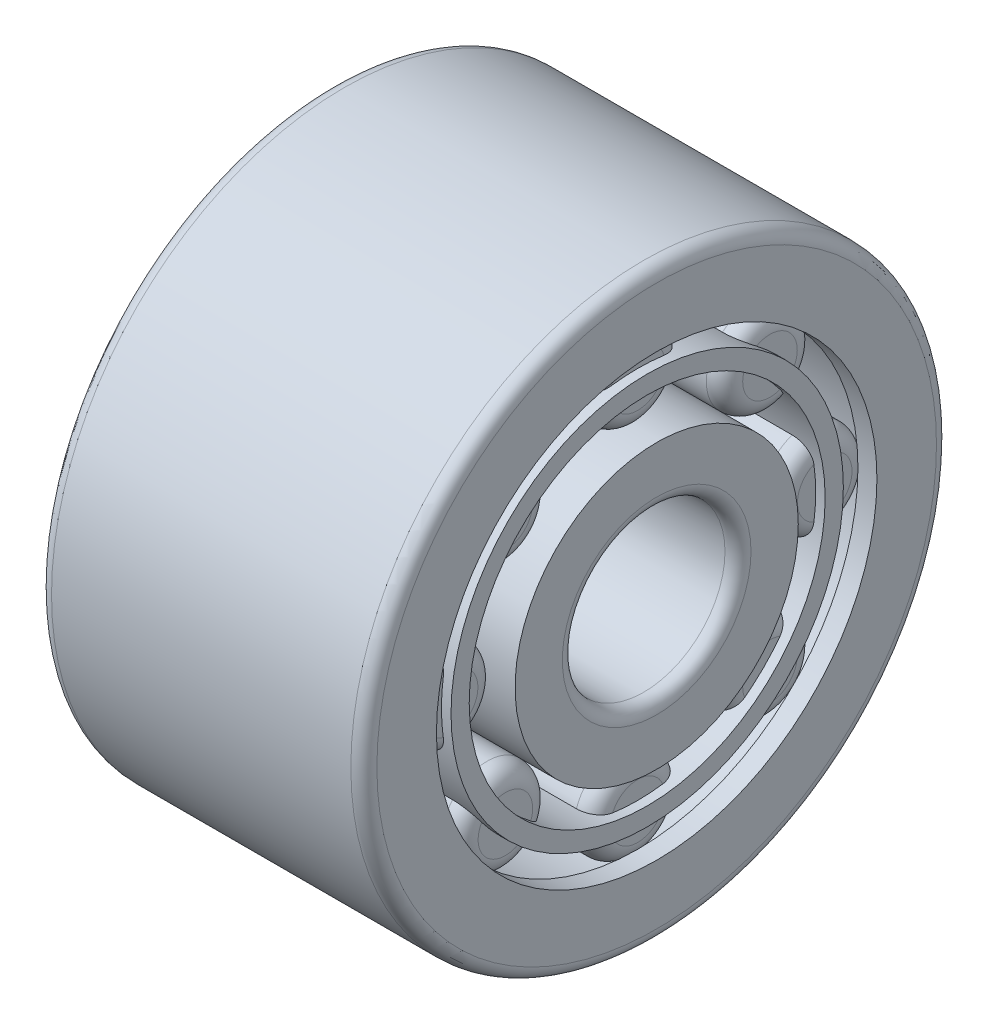
SolidWorks part; units mm, degrees
ref_plane "Plane1" through (0, 0, 0) normal (0, 0, 1) x (1, 0, 0)
ref_plane "Plane2" through (0, 0, 0) normal (0, 1, 0) x (1, 0, 0)
ref_plane "Plane3" through (0, 0, 0) normal (1, 0, 0) x (0, 0, -1)
sketch "Clipboard" plane through (0, 0, 0) normal (0, 0, 1) x (1, 0, 0)
  line L0 (-10, 0) -> (10, 0) construction
  line L1 (0, 0) -> (27.3694, -3.8465)
  line L2 (0, 0) -> (36.1572, 5.0816)
  line L3 (0, 0) -> (44.9449, -6.3166)
  line L4 (0, 0) -> (-22.3471, -0.7804)
  dimension "Race_OD" = 45.3866
  dimension "CLdia" = 36.5125
  dimension "Count" = 8
  dimension "Show_count" = 8
  dimension "Max_count" = 8
  dimension "Min_count" = 2
  dimension "Race_ID" = 27.6384
sketch "OutRacSke" plane through (0, 0, 0) normal (0, 0, 1) x (1, 0, 0)
  line L0 (-14.0229, 22.6933) -> (-14.0229, 21.4933)
  line L1 (-14.0229, 21.4933) -> (-15.875, 21.4933)
  line L2 (-15.875, 21.4933) -> (-15.875, 27.305)
  line L3 (-14.605, 28.575) -> (14.605, 28.575)
  line L4 (15.875, 27.305) -> (15.875, 21.4933)
  line L5 (15.875, 21.4933) -> (14.0229, 21.4933)
  line L6 (14.0229, 21.4933) -> (14.0229, 22.6933)
  line L7 (14.0229, 22.6933) -> (-14.0229, 22.6933)
  line L8 (-7.9375, 0) -> (7.9375, 0) construction
  arc A0 (-15.875, 27.305) -> (-14.605, 28.575) centre (-14.605, 27.305) cw
  arc A1 (14.605, 28.575) -> (15.875, 27.305) centre (14.605, 27.305) cw
  dimension "Radius" = 1.27
  dimension "OD" = 57.15
  dimension "Cyl_Len" = 28.0458
  dimension "Width" = 31.75
  dimension "halfWidth" = 15.875
  dimension "D1" = 14.0229
  dimension "Groove_Dp" = 1.2
  dimension "Race_OD" = 45.3866
revolve "OuterRace" add sketch "OutRacSke" angle 360 about L8
sketch "RolDetSke" plane through (0, 0, 0) normal (0, 0, 1) x (1, 0, 0)
  line L0 (-14.0229, 20.9188) -> (-14.0229, 18.2562)
  line L1 (-14.0229, 18.2562) -> (14.0229, 18.2562)
  line L2 (14.0229, 18.2562) -> (14.0229, 20.9188)
  line L3 (12.2479, 22.6938) -> (-12.2479, 22.6938)
  line L4 (-28.575, 18.2562) -> (28.575, 18.2562) construction
  arc A0 (14.0229, 20.9188) -> (12.2479, 22.6938) centre (12.2479, 20.9188) ccw
  arc A1 (-12.2479, 22.6938) -> (-14.0229, 20.9188) centre (-12.2479, 20.9188) ccw
  dimension "Cyl_Len" = 28.0458
  dimension "radius" = 1.775
  dimension "CLRad" = 18.2562
  dimension "Roller_diameter" = 8.8751
  dimension "halfCylLen" = 14.0229
revolve "RollerDetailed" add sketch "RolDetSke" angle 360 about L4
ref_axis "Axis1" through (-50, 0, 0) along (1, 0, 0)
sketch "RolSimSke" plane through (0, 25.4, 0) normal (0, 0, 1) x (1, 0, 0)
  line L0 (-14.0229, -4.4807) -> (-14.0229, -9.8058)
  line L1 (-25.4, -25.4) -> (25.4, -25.4) construction
  line L2 (14.0229, -9.8058) -> (14.0229, -4.4807)
  line L3 (12.2479, -2.7057) -> (-12.2479, -2.7057)
  line L5 (12.2479, -11.5808) -> (-12.2479, -11.5808)
  arc A0 (14.0229, -4.4807) -> (12.2479, -2.7057) centre (12.2479, -4.4807) ccw
  arc A1 (-12.2479, -2.7057) -> (-14.0229, -4.4807) centre (-12.2479, -4.4807) ccw
  arc A2 (14.0229, -9.8058) -> (12.2479, -11.5808) centre (12.2479, -9.8058) cw
  arc A3 (-12.2479, -11.5808) -> (-14.0229, -9.8058) centre (-12.2479, -9.8058) cw
  dimension "radius" = 1.775
  dimension "Roller_diameter" = 8.8751
  dimension "Bore" = 27.6384
  dimension "Cyl_Len" = 28.0458
  dimension "halfLength" = 14.0229
revolve "RollersSimplified" [suppressed] add sketch "RolSimSke" angle 360 about L1
sketch "InsRacSke" plane through (0, 0, 0) normal (0, 0, 1) x (1, 0, 0)
  line L2 (-15.875, 13.8192) -> (-15.875, 9.2075)
  line L4 (-14.605, 7.9375) -> (14.605, 7.9375)
  line L5 (15.875, 9.2075) -> (15.875, 13.8192)
  line L8 (15.875, 13.8192) -> (-15.875, 13.8192)
  line L9 (-7.9375, 0) -> (7.9375, 0) construction
  arc A0 (-15.875, 9.2075) -> (-14.605, 7.9375) centre (-14.605, 9.2075) ccw
  arc A2 (14.605, 7.9375) -> (15.875, 9.2075) centre (14.605, 9.2075) ccw
  dimension "halfWidth" = 15.875
  dimension "Race_ID" = 27.6384
  dimension "radius" = 1.27
  dimension "Bore" = 15.875
  dimension "Width_IR" = 31.75
revolve "InnerRace" add sketch "InsRacSke" angle 360 about L9
sketch "CagSpiSke" plane through (0, 0, 0) normal (0, 0, 1) x (1, 0, 0)
  line L0 (-17.1595, 0) -> (17.1595, 0) construction
  line L3 (-14.949, 17.3687) -> (14.949, 17.3687)
  line L4 (-14.949, 17.3687) -> (-14.949, 19.1438)
  line L5 (-14.949, 19.1438) -> (14.949, 19.1438)
  line L6 (14.949, 17.3687) -> (14.949, 19.1438)
  dimension "d2" = 34.7375
  dimension "cage_width" = 29.8979
  dimension "halfwidth" = 14.949
  dimension "cage_thickness" = 1.775
revolve "CageSpine" add sketch "CagSpiSke" angle 360 about L0
pattern_circular "RollersDetailed" count 8 every 45 about axis through (-50, 0, 0) along (1, 0, 0) of "RollerDetailed"
equation "\"halfWidth@OutRacSke\" =  \"Width@OutRacSke\" / 2"
equation "\"CLdia@Clipboard\" =  ( \"Race_OD@Clipboard\" + \"Race_ID@Clipboard\" )  / 2"
equation "\"CLRad@RolDetSke\" = ( \"Race_OD@Clipboard\" + \"Race_ID@Clipboard\" )  / 4"
equation "\"Roller_diameter@RolDetSke\" =  ( \"Race_OD@Clipboard\" -  \"Race_ID@Clipboard\" )  / 2 + .001"
equation "\"Roller_diameter@RolSimSke\" = ( \"Race_OD@Clipboard\" -  \"Race_ID@Clipboard\" )  / 2 + .001"
equation "\"radius@RolDetSke\" = \"Roller_diameter@RolDetSke\" / 5"
equation "\"radius@RolSimSke\" = \"Roller_diameter@RolSimSke\" / 5"
equation "\"Cyl_Len@OutRacSke\" = \"Cyl_Len@RolDetSke\""
equation "\"Cyl_Len@RolSimSke\" = \"Cyl_Len@RolDetSke\""
equation "\"halfCylLen@RolDetSke\" = \"Cyl_Len@RolDetSke\" / 2"
equation "\"D1@OutRacSke\" = \"Cyl_Len@OutRacSke\" / 2"
equation "\"cage_width@CagSpiSke\" =  ( \"Cyl_Len@RolDetSke\" + \"Width@OutRacSke\" )  / 2"
equation "\"halfwidth@CagSpiSke\" = \"cage_width@CagSpiSke\" / 2"
equation "\"cage_thickness@CagSpiSke\" = \"Roller_diameter@RolDetSke\" / 5"
equation "\"d2@CagSpiSke\" = \"CLRad@RolDetSke\" * 2 - \"cage_thickness@CagSpiSke\""
equation "\"Max_count@Clipboard\" = int( 3.14159265 / atn(( \"Roller_diameter@RolDetSke\" / 2) / sqr( \"CLRad@RolDetSke\"  *  \"CLRad@RolDetSke\" - ( \"Roller_diameter@RolDetSke\" / 2) *  ( \"Roller_diameter@RolDetSke\" / 2))))"
equation "\"Max_count@Clipboard\" = ((sgn( \"Max_count@Clipboard\" - \"Count@Clipboard\" )-1)*( \"Max_count@Clipboard\" - \"Count@Clipboard\" ))/-2+ \"Count@Clipboard\""
equation "\"Count@RollersDetailed\" = int( \"Show_count@Clipboard\" ) "
equation "\"Count@RollersDetailed\" = ((sgn( \"Count@RollersDetailed\" - \"Max_count@Clipboard\" )-1)*( \"Count@RollersDetailed\" - \"Max_count@Clipboard\" ))/-2+ \"Max_count@Clipboard\""
equation "\"Count@RollersDetailed\" = ((sgn( \"Count@RollersDetailed\" - \"Min_count@Clipboard\" )+1)*( \"Count@RollersDetailed\" - \"Min_count@Clipboard\"))/2 +\"Min_count@Clipboard\""
equation "\"Angle@RollersDetailed\" = 360.0 / \"Max_count@Clipboard\""
equation "\"Bore@RolSimSke\" = \"Race_ID@Clipboard\""
equation "\"Race_ID@InsRacSke\" = \"Race_ID@Clipboard\""
equation "\"halfWidth@InsRacSke\" = \"Width_IR@InsRacSke\" / 2"
equation "\"halfLength@RolSimSke\" = \"Cyl_Len@RolSimSke\" / 2"
equation "\"Race_OD@OutRacSke\" = \"Race_OD@Clipboard\""
equation "\"Width_IR@InsRacSke\" = \"Width@OutRacSke\""
equation "\"Angle@CageSpine\" =  \"Angle@RollersDetailed\" * ( \"Count@RollersDetailed\" -1 + int( \"Count@RollersDetailed\" / \"Max_count@Clipboard\" ) )  + 0.001 -  int( \"Count@RollersDetailed\" / \"Max_count@Clipboard\" ) * 0.001"
equation "\"Angle@CageSpine\" =  \"Angle@CageSpine\" * int( \"Min_count@Clipboard\" / 2) + int(1 / \"Min_count@Clipboard\")  * 0.001"
equation "\"radius@InsRacSke\" = \"Radius@OutRacSke\""
